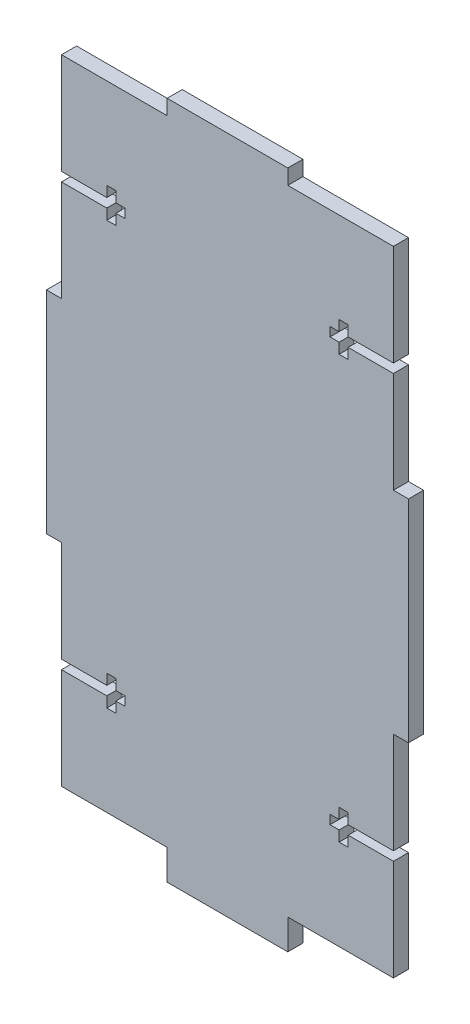
SolidWorks part; units mm, degrees
material "CA"
ref_plane "Alzado" through (0, 0, 0) normal (0, 0, 1) x (1, 0, 0)
ref_plane "Planta" through (0, 0, 0) normal (0, 1, 0) x (1, 0, 0)
ref_plane "Vista lateral" through (0, 0, 0) normal (1, 0, 0) x (0, 0, -1)
sketch "Croquis1" plane through (0, 0, 0) normal (0, 0, 1) x (1, 0, 0)
  line L0 (0, 0) -> (35, 0)
  line L1 (35, 0) -> (35, -10)
  line L2 (35, -10) -> (75, -10)
  line L3 (75, -10) -> (75, 0)
  line L4 (75, 0) -> (110, 0)
  line L5 (110, 0) -> (110, 33.5)
  line L6 (110, 33.5) -> (95, 33.5)
  line L7 (95, 33.5) -> (95, 30)
  line L8 (95, 30) -> (92, 30)
  line L9 (92, 30) -> (92, 33.5)
  line L10 (92, 33.5) -> (89, 33.5)
  line L11 (89, 33.5) -> (89, 36.5)
  line L12 (89, 36.5) -> (92, 36.5)
  line L13 (92, 36.5) -> (92, 40)
  line L14 (92, 40) -> (95, 40)
  line L15 (95, 40) -> (95, 36.5)
  line L16 (95, 36.5) -> (110, 36.5)
  line L17 (110, 36.5) -> (110, 70)
  line L18 (110, 70) -> (115, 70)
  line L19 (115, 70) -> (115, 140)
  line L20 (115, 140) -> (110, 140)
  line L21 (110, 140) -> (110, 173.5)
  line L23 (95, 170) -> (95, 173.5)
  line L24 (92, 170) -> (95, 170)
  line L25 (92, 173.5) -> (92, 170)
  line L26 (89, 173.5) -> (92, 173.5)
  line L27 (95, 173.5) -> (110, 173.5)
  line L28 (89, 176.5) -> (89, 173.5)
  line L29 (92, 176.5) -> (89, 176.5)
  line L30 (92, 180) -> (92, 176.5)
  line L31 (95, 180) -> (92, 180)
  line L32 (95, 176.5) -> (95, 180)
  line L33 (110, 176.5) -> (95, 176.5)
  line L34 (110, 210) -> (110, 176.5)
  line L35 (75, 210) -> (110, 210)
  line L36 (75, 215) -> (75, 210)
  line L37 (35, 215) -> (75, 215)
  line L38 (35, 210) -> (35, 215)
  line L39 (0, 210) -> (35, 210)
  line L40 (15, 36.5) -> (0, 36.5)
  line L41 (15, 40) -> (15, 36.5)
  line L42 (18, 40) -> (15, 40)
  line L43 (18, 36.5) -> (18, 40)
  line L44 (21, 36.5) -> (18, 36.5)
  line L45 (21, 33.5) -> (21, 36.5)
  line L46 (18, 33.5) -> (21, 33.5)
  line L47 (18, 30) -> (18, 33.5)
  line L48 (15, 30) -> (18, 30)
  line L49 (15, 33.5) -> (15, 30)
  line L50 (0, 33.5) -> (15, 33.5)
  line L51 (0, 0) -> (0, 33.5)
  line L52 (-5, 140) -> (0, 140)
  line L53 (-5, 70) -> (-5, 140)
  line L54 (0, 70) -> (-5, 70)
  line L55 (0, 36.5) -> (0, 70)
  line L56 (0, 210) -> (0, 176.5)
  line L57 (0, 176.5) -> (15, 176.5)
  line L58 (15, 176.5) -> (15, 180)
  line L59 (15, 180) -> (18, 180)
  line L60 (18, 180) -> (18, 176.5)
  line L61 (18, 176.5) -> (21, 176.5)
  line L62 (21, 176.5) -> (21, 173.5)
  line L63 (15, 173.5) -> (0, 173.5)
  line L64 (21, 173.5) -> (18, 173.5)
  line L65 (18, 173.5) -> (18, 170)
  line L66 (18, 170) -> (15, 170)
  line L67 (15, 170) -> (15, 173.5)
  line L68 (0, 140) -> (0, 173.5)
  dimension "D1" = 35
  dimension "D2" = 40
  dimension "D3" = 35
  dimension "D4" = 10
  dimension "D5" = 33.5
  dimension "D6" = 15
  dimension "D7" = 3
  dimension "D8" = 3.5
  dimension "D9" = 3
  dimension "D10" = 3
  dimension "D11" = 3.5
  dimension "D12" = 33.5
  dimension "D13" = 5
  dimension "D14" = 70
  dimension "D15" = 33.5
  dimension "D16" = 5
  dimension "D17" = 5
  dimension "D18" = 35
  dimension "D19" = 33.5
extrude "Saliente-Extruir1" add sketch "Croquis1" along normal blind 5 contours L68 L63 L67 L66 L65 L64 L62 L61 L60 L59 L58 L57 L56 L39 L38 L37 L36 L35 L34 L33 L32 L31 L30 L29 L28 L26 L25 L24 L23 L27 L21 L20 L19 L18 L17 L16 L15 L14 L13 L12 L11 L10 L9 L8 L7 L6 L5 L4 L3 L2 L1 L0 L51 L50 L49 L48 L47 L46 L45 L44 L43 L42 L41 L40 L55 L54 L53 L52
